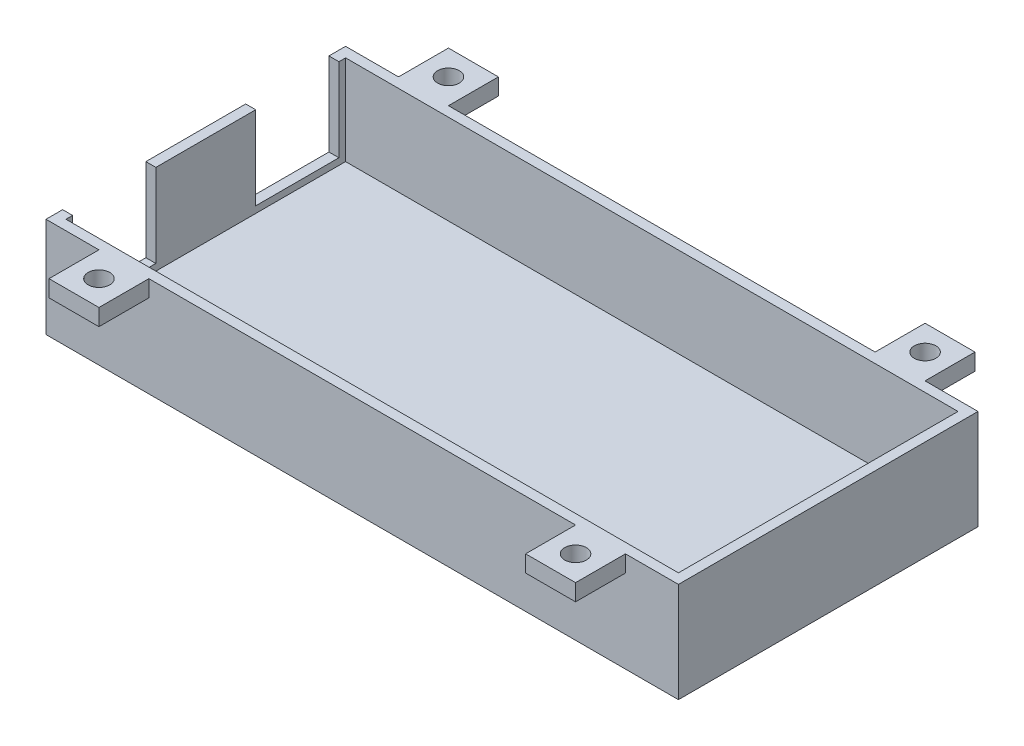
SolidWorks part; units mm, degrees
ref_plane "Front Plane" through (0, 0, 0) normal (0, 0, 1) x (1, 0, 0)
ref_plane "Top Plane" through (0, 0, 0) normal (0, 1, 0) x (1, 0, 0)
ref_plane "Right Plane" through (0, 0, 0) normal (1, 0, 0) x (0, 0, -1)
sketch "Sketch2" plane through (0, 0, 0) normal (0, 1, 0) x (1, 0, 0)
  line L1 (-95, 45) -> (95, 45)
  line L2 (-95, 45) -> (-95, -45)
  line L3 (-95, -45) -> (95, -45)
  line L4 (95, 45) -> (95, -45)
  line L5 (-95, 45) -> (95, -45) construction
  line L6 (-95, -45) -> (95, 45) construction
  point P0 (0, 0)
  dimension "D1" = 90
  dimension "D2" = 190
extrude "Boss-Extrude1" add sketch "Sketch2" along normal blind 5
sketch "Sketch3" plane through (0, 5, 0) normal (0, 1, 0) x (1, 0, 0)
  line L1 (-95, 45) -> (95, 45)
  line L2 (-95, 45) -> (-95, -45)
  line L3 (-95, -45) -> (95, -45)
  line L4 (95, 45) -> (95, -45)
  line L5 (-95, 45) -> (95, -45) construction
  line L6 (-95, -45) -> (95, 45) construction
  line L7 (-90, 40) -> (90, 40)
  line L8 (-90, 40) -> (-90, -40)
  line L9 (-90, -40) -> (90, -40)
  line L10 (90, 40) -> (90, -40)
  line L11 (-90, 40) -> (90, -40) construction
  line L12 (-90, -40) -> (90, 40) construction
  point P0 (0, 0)
  point P7 (0, 0)
  dimension "D1" = 5
  dimension "D2" = 5
  dimension "D3" = 5
  dimension "D4" = 5
extrude "Boss-Extrude2" add sketch "Sketch3" along normal blind 25
sketch "Sketch5" plane through (-90, 0, 0) normal (1, 0, 0) x (0, 0, -1)
  line L0 (40, 30) -> (-40, 30) construction
  line L2 (-15, 5) -> (-15, 30)
  line L4 (15, 5) -> (15, 30)
  line L9 (40, 5) -> (-40, 5) construction
  line L10 (-15, 30) -> (-40, 30)
  line L11 (-40, 30) -> (-40, 5)
  line L12 (-40, 5) -> (-15, 5)
  line L13 (15, 5) -> (40, 5)
  line L14 (40, 5) -> (40, 30)
  line L15 (40, 30) -> (15, 30)
  point P0 (0, 0)
  dimension "D1" = 30
  dimension "D2" = 25
extrude "Cut-Extrude1" cut sketch "Sketch5" against normal up to surface (5 mm away) up to face at (-95, 15, 0)
sketch "Sketch6" plane through (0, 30, 0) normal (0, 1, 0) x (1, 0, 0)
  line L0 (95, 45) -> (-95, 45) construction
  line L1 (-79.0935, 45) -> (-64.0935, 45)
  line L2 (-79.0935, 45) -> (-79.0935, 60)
  line L3 (-79.0935, 60) -> (-64.0935, 60)
  line L4 (-64.0935, 45) -> (-64.0935, 60)
  line L5 (0, 0) -> (-64.0935, 0) construction
  line L6 (-79.0935, -60) -> (-64.0935, -60)
  line L7 (-79.0935, -45) -> (-79.0935, -60)
  line L8 (-79.0935, -45) -> (-64.0935, -45)
  line L9 (-64.0935, -45) -> (-64.0935, -60)
  line L10 (0, 0) -> (0, 27.9699) construction
  line L11 (64.0935, -45) -> (64.0935, -60)
  line L12 (79.0935, -60) -> (64.0935, -60)
  line L13 (79.0935, -45) -> (79.0935, -60)
  line L14 (79.0935, -45) -> (64.0935, -45)
  line L15 (79.0935, 45) -> (64.0935, 45)
  line L16 (79.0935, 45) -> (79.0935, 60)
  line L17 (79.0935, 60) -> (64.0935, 60)
  line L18 (64.0935, 45) -> (64.0935, 60)
  circle A0 centre (-71.5935, 52.5) radius 3.25
  circle A1 centre (-71.5935, -52.5) radius 3.25
  circle A2 centre (71.5935, -52.5) radius 3.25
  circle A3 centre (71.5935, 52.5) radius 3.25
  dimension "D3" = 6.5
  dimension "D1" = 15
  dimension "D2" = 15
extrude "Boss-Extrude3" add sketch "Sketch6" against normal blind 5
sketch "Sketch8" plane through (0, 30, 0) normal (0, 1, 0) x (1, 0, 0)
  line L0 (-64.0935, -45) -> (64.0935, -45) construction
  line L1 (92, -42) -> (-92, -42)
  line L2 (92, -42) -> (92, 42)
  line L3 (92, 42) -> (-92, 42)
  line L4 (-92, -42) -> (-92, 42)
  line L5 (92, -42) -> (-92, 42) construction
  line L6 (92, 42) -> (-92, -42) construction
  line L7 (95, -45) -> (95, 45) construction
  point P0 (0, 0)
  dimension "D1" = 3
  dimension "D2" = 3
extrude "Cut-Extrude2" cut sketch "Sketch8" against normal blind 27 contours L1 L4 L3 L2
